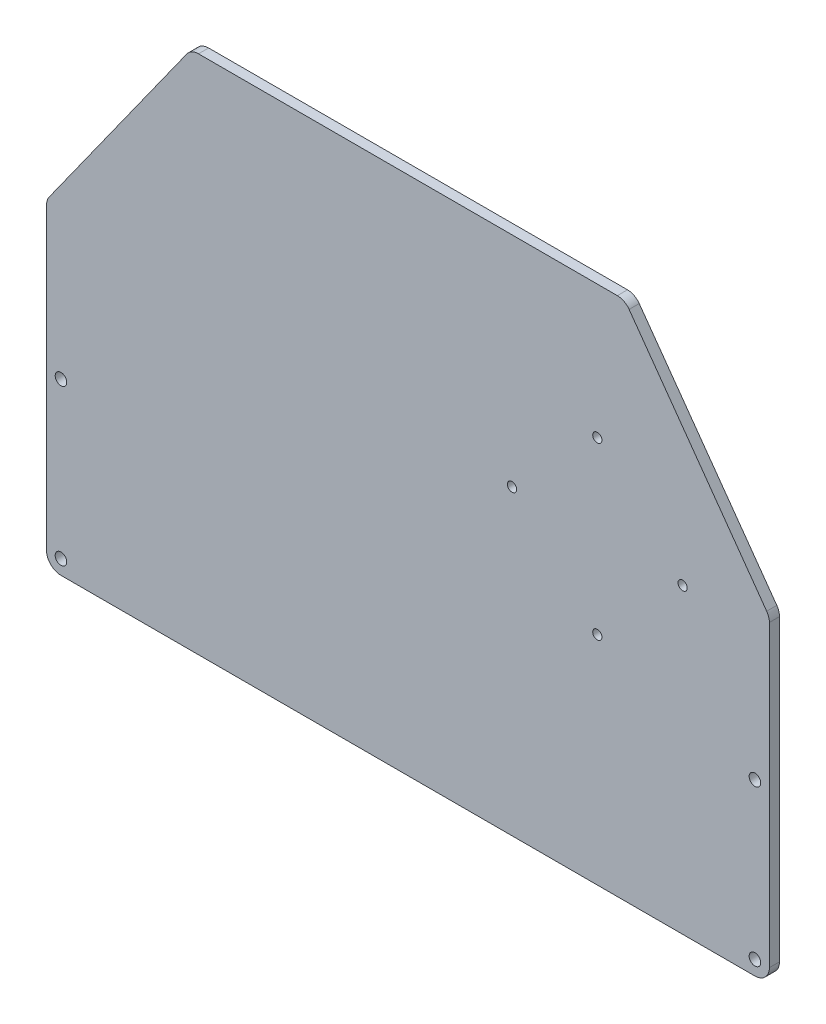
SolidWorks part; units mm, degrees
ref_plane "Plan de face" through (0, 0, 0) normal (0, 0, 1) x (1, 0, 0)
ref_plane "Plan de dessus" through (0, 0, 0) normal (0, 1, 0) x (1, 0, 0)
ref_plane "Plan de droite" through (0, 0, 0) normal (1, 0, 0) x (0, 0, -1)
sketch "Esquisse1" plane through (0, 0, 0) normal (0, 0, 1) x (1, 0, 0)
  line L1 (5, 0) -> (245, 0)
  line L2 (0, 5) -> (0, 305)
  line L3 (0, 305) -> (250, 305)
  line L4 (250, 5) -> (250, 305)
  arc A0 (250, 5) -> (245, 0) centre (245, 5) cw
  arc A1 (5, 0) -> (0, 5) centre (5, 5) cw
  point P7 (250, 0)
  point P10 (0, 0)
  dimension "D2" = 5
  dimension "D3" = 5
  dimension "D1" = 250
  dimension "D4" = 300
extrude "Boss.-Extru.1" add sketch "Esquisse1" along normal blind 3.5
sketch "Esquisse2" plane through (0, 0, 3.5) normal (0, 0, 1) x (1, 0, 0)
  line L0 (-19.0099, 5) -> (402.2953, 5) construction
  line L1 (5, 0) -> (245, 0) construction
  line L2 (5, -25.1291) -> (5, 139.966) construction
  line L3 (0, 305) -> (0, 5) construction
  line L4 (245, -22.1166) -> (245, 94.5536) construction
  line L5 (250, 5) -> (250, 305) construction
  line L6 (-9.3926, 58.8) -> (267.0784, 58.8) construction
  circle A0 centre (5, 5) radius 2
  circle A1 centre (245, 5) radius 2
  circle A2 centre (5, 58.8) radius 2
  circle A3 centre (245, 58.8) radius 2
  dimension "D1" = 4
  dimension "D2" = 4
  dimension "D7" = 4
  dimension "D8" = 4
  dimension "D3" = 5
  dimension "D4" = 5
  dimension "D5" = 5
  dimension "D6" = 53.8
extrude "Enlèv. mat.-Extru.1" cut sketch "Esquisse2" against normal through all
sketch "Esquisse3" plane through (0, 0, 3.5) normal (0, 0, 1) x (1, 0, 0)
  line L0 (0, 110) -> (50, 180)
  line L1 (50, 180) -> (200, 180)
  line L2 (200, 180) -> (250, 110)
  line L3 (125, 632.4465) -> (125, -22.4465) construction
  line L4 (250, 305) -> (0, 305) construction
  line L5 (0, 305) -> (0, 5) construction
  line L6 (250, 5) -> (250, 305) construction
  line L7 (5, 0) -> (245, 0) construction
  point P8 (125, 305)
  point P9 (125, 180)
  dimension "D1" = 110
  dimension "D2" = 110
  dimension "D3" = 150
  dimension "D4" = 180
  dimension "D5" = 180
extrude "Enlèv. mat.-Extru.2" cut sketch "Esquisse3" against normal through all and the other way through all
fillet "Congé1" radius 5 4 edges at (250, 110, 1.75) (200, 180, 1.75) (50, 180, 1.75) (0, 110, 1.75)
sketch "Esquisse4" plane through (0, 0, 3.5) normal (0, 0, 1) x (1, 0, 0)
  line L1 (190.499, 53.7022) -> (190.499, 163.5121) construction
  line L2 (161.0233, 104.5) -> (239.0024, 104.5) construction
  line L3 (250, 5) -> (250, 108.3977) construction
  line L4 (5, 0) -> (245, 0) construction
  circle A0 centre (220, 104.5) radius 1.6
  circle A1 centre (190.499, 134) radius 1.6
  circle A2 centre (160.998, 104.5) radius 1.6
  circle A3 centre (190.499, 75) radius 1.6
  dimension "D7" = 3.2
  dimension "D8" = 3.2
  dimension "D9" = 3.2
  dimension "D10" = 3.2
  dimension "D2" = 30
  dimension "D3" = 59
  dimension "D4" = 41.72
  dimension "D5" = 41.72
  dimension "D6" = 41.72
  dimension "D11" = 75
extrude "Enlèv. mat.-Extru.4" cut sketch "Esquisse4" against normal through all
